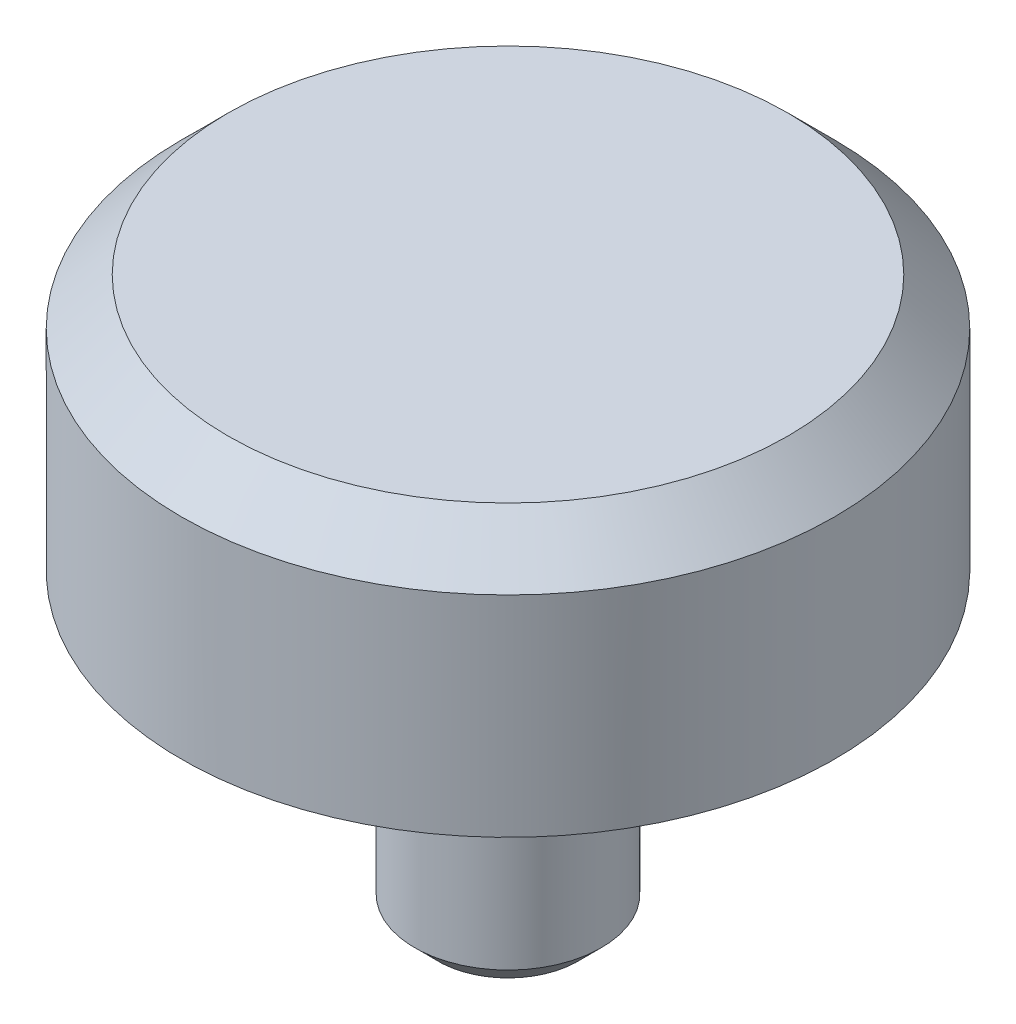
SolidWorks part; units mm, degrees
ref_plane "Front Plane" through (0, 0, 0) normal (0, 0, 1) x (1, 0, 0)
ref_plane "Top Plane" through (0, 0, 0) normal (0, 1, 0) x (1, 0, 0)
ref_plane "Right Plane" through (0, 0, 0) normal (1, 0, 0) x (0, 0, -1)
sketch "Sketch1" plane through (0, 0, 0) normal (0, 0, 1) x (1, 0, 0)
  line L0 (0, 0) -> (0, 24)
  line L1 (0, 24) -> (14, 24)
  line L2 (0, 0) -> (4, 0)
  line L3 (4, 0) -> (4, 13)
  line L4 (4, 13) -> (14, 13)
  line L5 (14, 13) -> (14, 24)
revolve "Revolve1" add sketch "Sketch1" angle 360 about L0
cosmetic thread "Cosmetic Thread1" parameters "D1"=9, "D2"=6.619
fillet "Fillet1" radius 1 1 edges at (0, 13, -4)
chamfer "Chamfer1" distance 2 angle 45 1 edges at (0, 24, -14)
chamfer "Chamfer2" distance 1 angle 45 1 edges at (0, 0, -4)
